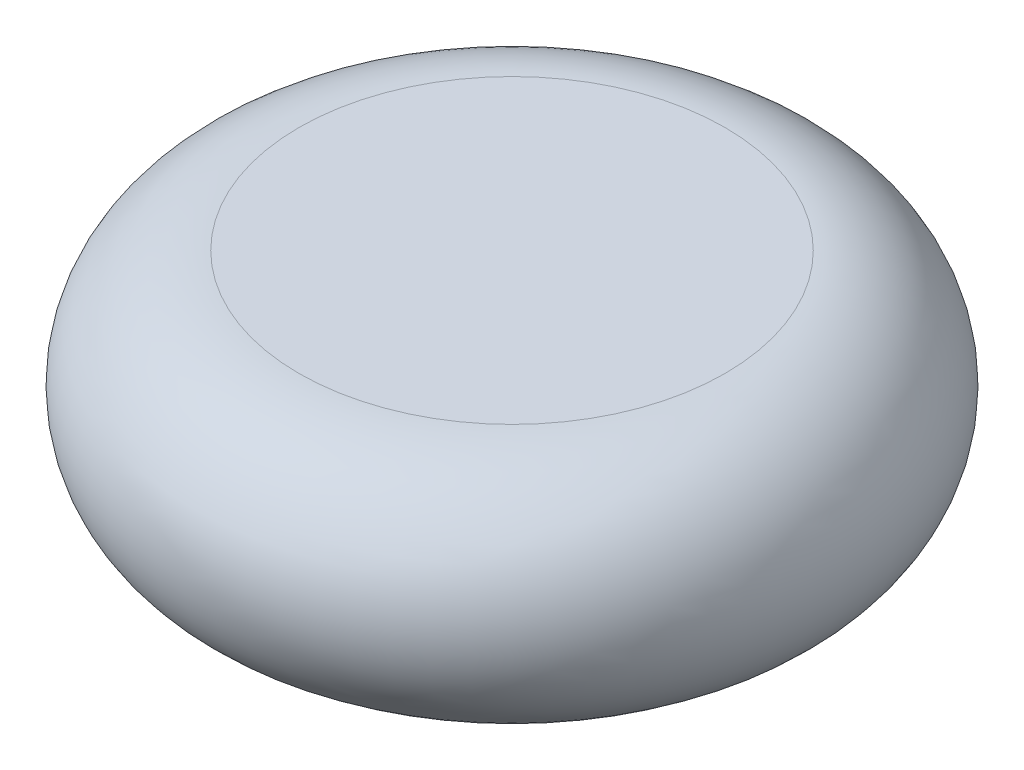
SolidWorks part; units mm, degrees
ref_plane "Front Plane" through (0, 0, 0) normal (0, 0, 1) x (1, 0, 0)
ref_plane "Top Plane" through (0, 0, 0) normal (0, 1, 0) x (1, 0, 0)
ref_plane "Right Plane" through (0, 0, 0) normal (1, 0, 0) x (0, 0, -1)
sketch "Sketch1" plane through (0, 0, 0) normal (0, 1, 0) x (1, 0, 0)
  circle A0 centre (0, 0) radius 228.6
  dimension "D1" = 457.2
extrude "Boss-Extrude1" add sketch "Sketch1" along normal blind 250
ref_axis "Axis1" through (0, 445.3109, 0) along (0, -1, 0)
sketch "Sketch2" plane through (0, 0, 0) normal (0, 0, 1) x (1, 0, 0)
  line L0 (228.6, 250) -> (228.6, 0)
  arc A0 (228.6, 0) -> (228.6, 250) centre (228.6, 125) ccw
revolve "Revolve1" add sketch "Sketch2" angle 360 about axis through (0, 445.3109, 0) along (0, -1, 0)
